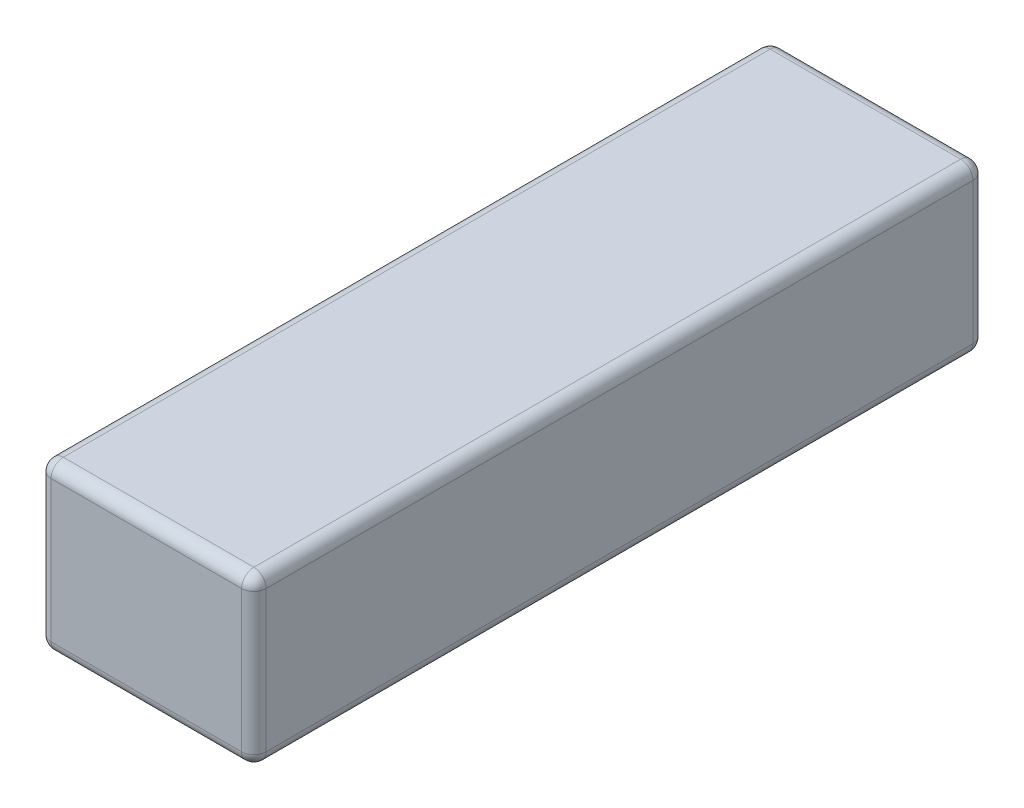
SolidWorks part; units mm, degrees
ref_plane "前视基准面" through (0, 0, 0) normal (0, 0, 1) x (1, 0, 0)
ref_plane "上视基准面" through (0, 0, 0) normal (0, 1, 0) x (1, 0, 0)
ref_plane "右视基准面" through (0, 0, 0) normal (1, 0, 0) x (0, 0, -1)
sketch "草图1" plane through (-9.7407, 0, 0) normal (0, 0, 1) x (1, 0, 0)
  line L1 (-104.4783, 54.8913) -> (-69.4783, 54.8913)
  line L2 (-104.4783, 54.8913) -> (-104.4783, 27.8913)
  line L3 (-104.4783, 27.8913) -> (-69.4783, 27.8913)
  line L4 (-69.4783, 54.8913) -> (-69.4783, 27.8913)
  dimension "D1" = 27
  dimension "D2" = 35
extrude "凸台-拉伸1" add sketch "草图1" along normal blind 119
fillet "圆角2" radius 2 12 edges at (-96.7189, 27.8913, 0) (-114.2189, 27.8913, 59.5) (-114.2189, 41.3913, 0) (-96.7189, 27.8913, 119) (-114.2189, 41.3913, 119) (-79.2189, 27.8913, 59.5) (-79.2189, 41.3913, 119) (-79.2189, 41.3913, 0) (-79.2189, 54.8913, 59.5) (-96.7189, 54.8913, 119) (-114.2189, 54.8913, 59.5) (-96.7189, 54.8913, 0)
